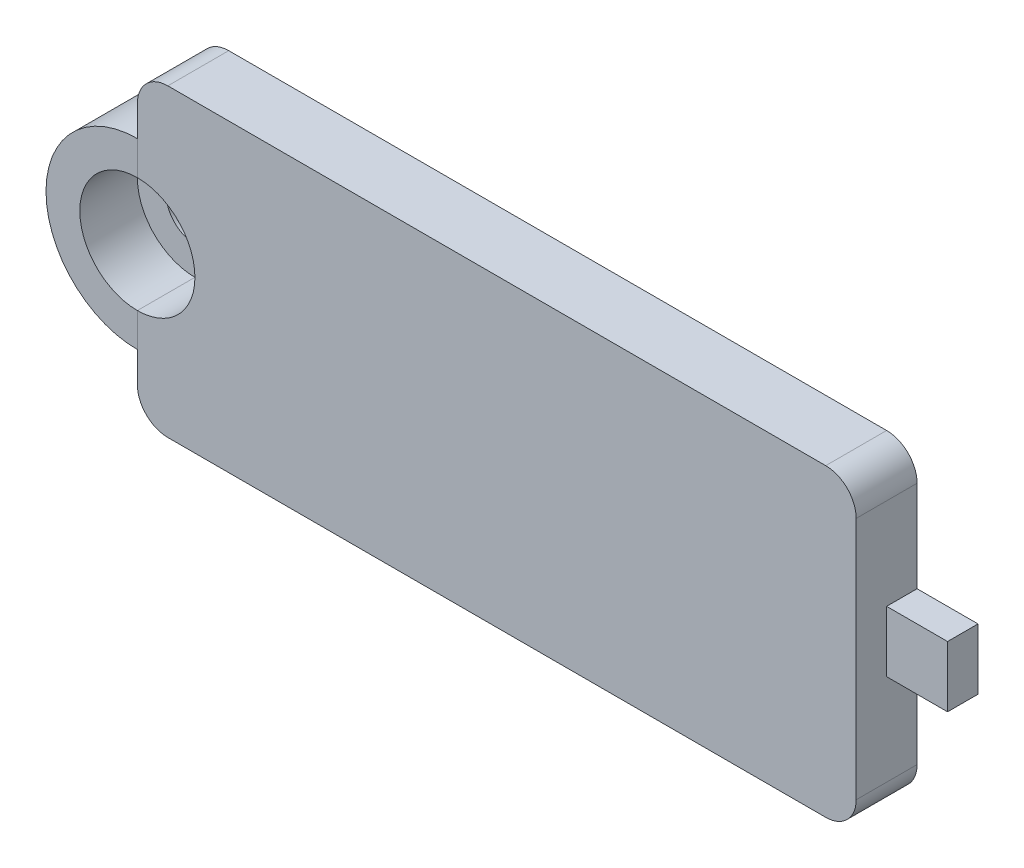
SolidWorks part; units mm, degrees
ref_plane "Front Plane" through (0, 0, 0) normal (0, 0, 1) x (1, 0, 0)
ref_plane "Top Plane" through (0, 0, 0) normal (0, 1, 0) x (1, 0, 0)
ref_plane "Right Plane" through (0, 0, 0) normal (1, 0, 0) x (0, 0, -1)
sketch "Sketch1" plane through (0, 0, 0) normal (0, 0, 1) x (1, 0, 0)
  line L1 (-18.7325, -7.9375) -> (18.7325, -7.9375)
  line L2 (-18.7325, -7.9375) -> (-18.7325, 7.9375)
  line L3 (-18.7325, 7.9375) -> (18.7325, 7.9375)
  line L4 (18.7325, -7.9375) -> (18.7325, 7.9375)
  line L5 (-18.7325, -7.9375) -> (18.7325, 7.9375) construction
  line L6 (-18.7325, 7.9375) -> (18.7325, -7.9375) construction
  point P0 (0, 0)
  dimension "D1" = 37.465
  dimension "D2" = 15.875
extrude "Boss-Extrude1" add sketch "Sketch1" along normal blind 3.175
sketch "Sketch2" plane through (0, 0, 3.175) normal (0, 0, 1) x (1, 0, 0)
  line L0 (-18.7325, 4.7625) -> (-18.7325, -4.7625)
  line L6 (-18.7325, 7.9375) -> (-18.7325, 4.7625) construction
  line L7 (-18.7325, 7.9375) -> (-18.7325, -7.9375) construction
  line L8 (-18.7325, -7.9375) -> (-18.7325, -4.7625) construction
  arc A2 (-18.7325, 4.7625) -> (-18.7325, -4.7625) centre (-18.7325, 0) ccw
  dimension "D2" = 4.7625
extrude "Boss-Extrude2" add sketch "Sketch2" against normal blind 3.175 separate body
hole_wizard "CBORE for #00 Binding Head Machine Screw1" positions "Sketch3" profile "Sketch4" counterbore size "#00" standard "ANSI Inch" end condition through all
sketch "Sketch3" plane through (0, 0, 3.175) normal (0, 0, 1) x (1, 0, 0)
  line L3 (-18.7325, 7.9375) -> (-18.7325, -7.9375) construction
  point P0 (-18.7325, 0)
  point P3 (0, 0)
  point P7 (0, 0)
  point P8 (18.8958, 1.2272)
  point P9 (0, 0)
  point P13 (0, 0)
  point P16 (0, 0)
sketch "Sketch4" plane through (-18.7325, 0, 3.175) normal (1, 0, 0) x (0, -1, 0)
  line L0 (0, 0) -> (0, 3.175)
  line L1 (0, 3.175) -> (1.5, 3.175)
  line L3 (1.5, 3.175) -> (1.5, 3)
  line L4 (1.5, 3) -> (3, 3)
  line L5 (3, 3) -> (3, 0)
  line L7 (3, 0) -> (0, 0)
  line L11 (0, -6.35) -> (0, 107.95) construction
  dimension "Thru Hole Dia." = 3
  dimension "Thru Hole Depth" = 3.175
  dimension "C'Bore Dia." = 6
  dimension "C'Bore Depth" = 3
fillet "Fillet2" radius 1.5875 4 edges at (-18.7325, -7.9375, 1.5875) (18.7325, -7.9375, 1.5875) (18.7325, 7.9375, 1.5875) (-18.7325, 7.9375, 1.5875)
sketch "Sketch5" plane through (0, 0, 0) normal (0, 0, -1) x (-1, 0, 0)
  line L0 (-18.7325, -6.35) -> (-18.7325, 6.35) construction
  line L1 (-18.7325, 1.5875) -> (-21.9075, 1.5875)
  line L2 (-18.7325, 1.5875) -> (-18.7325, -1.5875)
  line L3 (-18.7325, -1.5875) -> (-21.9075, -1.5875)
  line L4 (-21.9075, 1.5875) -> (-21.9075, -1.5875)
  point P7 (-18.7325, 0)
  dimension "D1" = 3.175
  dimension "D2" = 3.175
extrude "Boss-Extrude3" add sketch "Sketch5" against normal blind 1.5875
